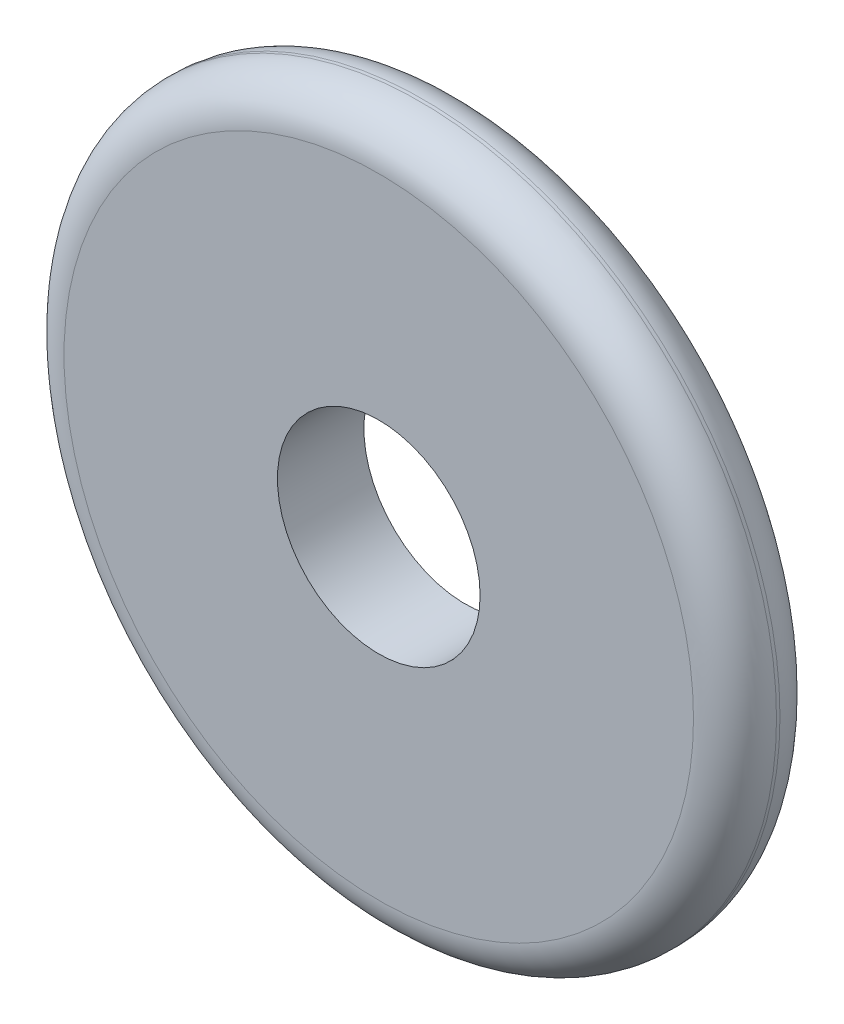
SolidWorks part; units mm, degrees
ref_plane "Plan de face" through (0, 0, 0) normal (0, 0, 1) x (1, 0, 0)
ref_plane "Plan de dessus" through (0, 0, 0) normal (0, 1, 0) x (1, 0, 0)
ref_plane "Plan de droite" through (0, 0, 0) normal (1, 0, 0) x (0, 0, -1)
sketch "Esquisse1" plane through (0, 0, 0) normal (0, 0, 1) x (1, 0, 0)
  circle A0 centre (0, 0) radius 14.65
  circle A1 centre (0, 0) radius 51.5
extrude "Boss.-Extru.1" add sketch "Esquisse1" along normal blind 12.5
fillet "Congé1" radius 6 2 edges at (51.5, 0, 0) (51.5, 0, 12.5)
